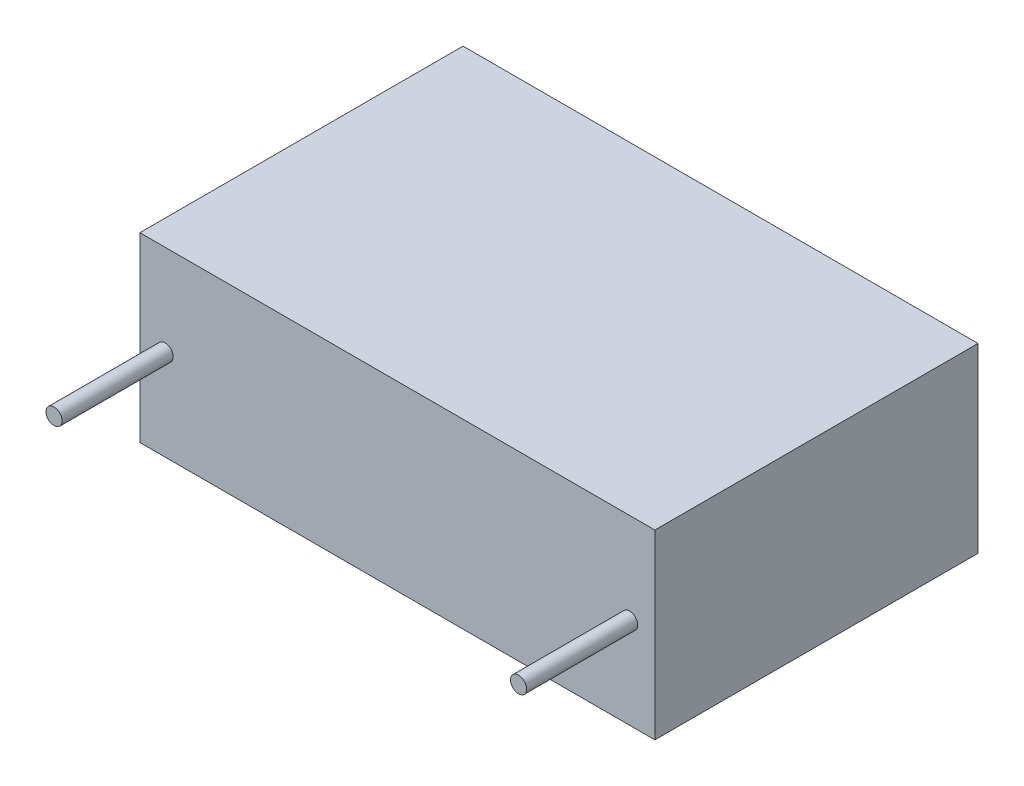
SolidWorks part; units mm, degrees
ref_plane "Спереди" through (0, 0, 0) normal (0, 0, 1) x (1, 0, 0)
ref_plane "Сверху" through (0, 0, 0) normal (0, 1, 0) x (1, 0, 0)
ref_plane "Справа" through (0, 0, 0) normal (1, 0, 0) x (0, 0, -1)
sketch "Эскиз1" plane through (0, 0, 0) normal (0, 0, 1) x (1, 0, 0)
  line L1 (0, 0) -> (25.5, 0)
  line L2 (0, 0) -> (0, 9)
  line L3 (0, 9) -> (25.5, 9)
  line L4 (25.5, 0) -> (25.5, 9)
  dimension "D1" = 9
  dimension "D2" = 25.5
extrude "Вытянуть1" add sketch "Эскиз1" along normal blind 16
sketch "Эскиз2" plane through (0, 0, 16) normal (0, 0, 1) x (1, 0, 0)
  line L0 (-0.6613, 4.5) -> (24.2043, 4.5) construction
  line L1 (0, 0) -> (25.5, 0) construction
  line L2 (25.5, 9) -> (0, 9) construction
  line L3 (12.75, 10.4113) -> (12.75, -0.9059) construction
  line L4 (0, 9) -> (0, 0) construction
  line L5 (25.5, 0) -> (25.5, 9) construction
  circle A0 centre (1.25, 4.5) radius 0.4
  circle A1 centre (24.25, 4.5) radius 0.4
  dimension "D1" = 23
  dimension "D2" = 0.8
extrude "Вытянуть2" add sketch "Эскиз2" along normal blind 5.5
